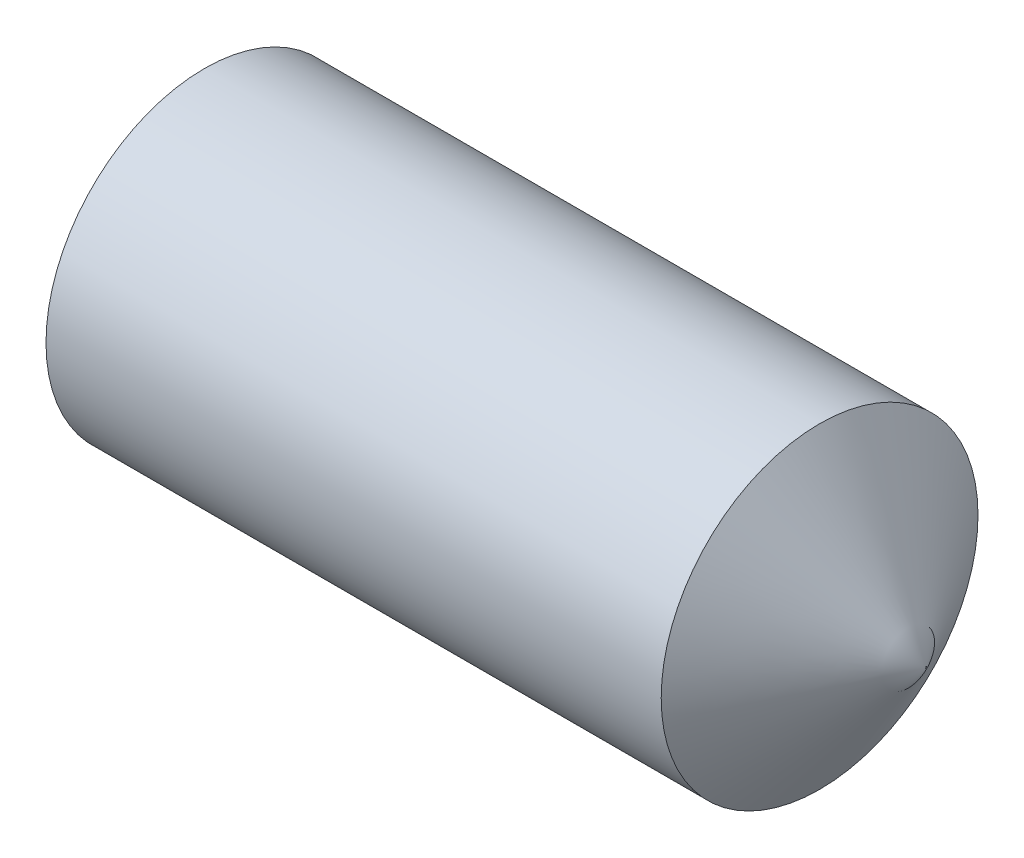
SolidWorks part; units mm, degrees
ref_plane "Front Plane" through (0, 0, 0) normal (0, 0, 1) x (1, 0, 0)
ref_plane "Top Plane" through (0, 0, 0) normal (0, 1, 0) x (1, 0, 0)
ref_plane "Right Plane" through (0, 0, 0) normal (1, 0, 0) x (0, 0, -1)
sketch "Sketch1" plane through (0, 0, 0) normal (0, 1, 0) x (1, 0, 0)
  line L0 (0, 0) -> (95.7627, 0) construction
  line L1 (0, 0) -> (0, 21.0244)
  line L2 (0, 21.0244) -> (81.656, 21.0244)
  line L3 (81.656, 21.0244) -> (95.7627, 0)
  line L4 (0, 0) -> (95.7627, 0)
revolve "Revolve1" add sketch "Sketch1" angle 360 about L0
